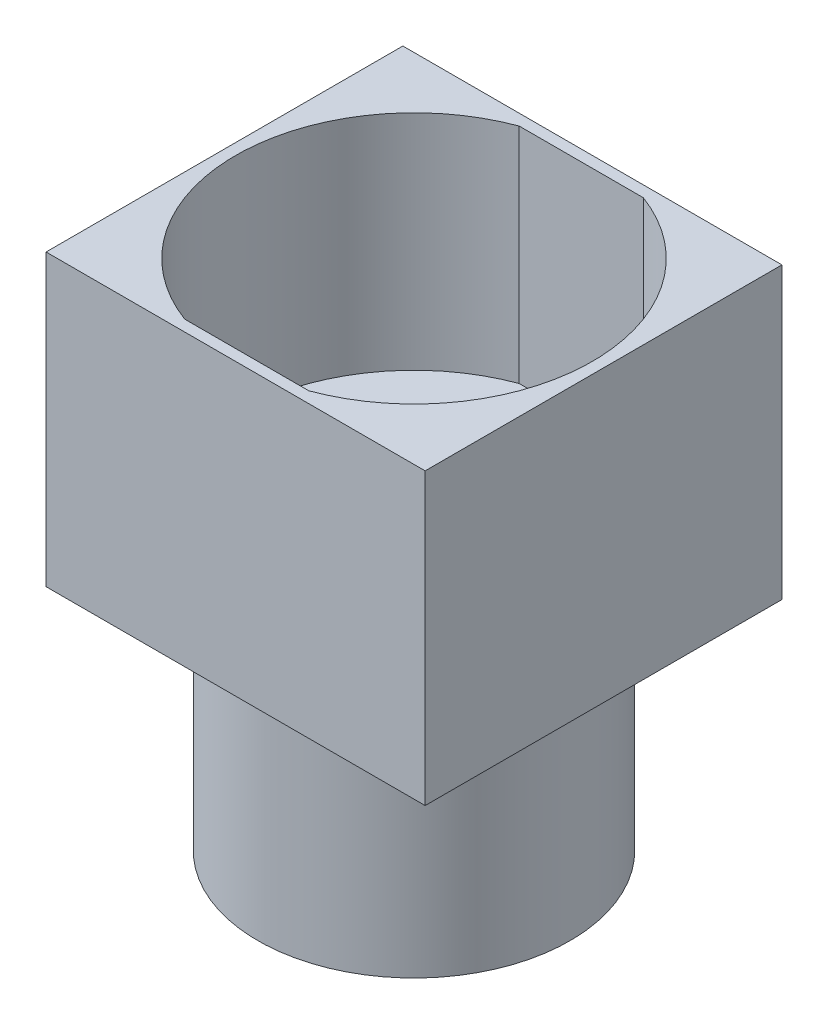
SolidWorks part; units mm, degrees
ref_plane "Front Plane" through (0, 0, 0) normal (0, 0, 1) x (1, 0, 0)
ref_plane "Top Plane" through (0, 0, 0) normal (0, 1, 0) x (1, 0, 0)
ref_plane "Right Plane" through (0, 0, 0) normal (1, 0, 0) x (0, 0, -1)
sketch "Sketch1" plane through (0, 0, 0) normal (0, 1, 0) x (1, 0, 0)
  circle A0 centre (0, 0) radius 4
  circle A1 centre (0, 0) radius 7
  dimension "D1" = 8
  dimension "D2" = 14
extrude "Boss-Extrude1" add sketch "Sketch1" along normal blind 13
sketch "Sketch2" plane through (0, 13, 0) normal (0, 1, 0) x (1, 0, 0)
  line L0 (-8, 7.5) -> (-8, -7.5) construction
  line L1 (-8.5, 8) -> (8.5, 8)
  line L2 (-8.5, 8) -> (-8.5, -8)
  line L3 (-8.5, -8) -> (8.5, -8)
  line L4 (8.5, 8) -> (8.5, -8)
  line L5 (-8.5, 8) -> (8.5, -8) construction
  line L6 (-8.5, -8) -> (8.5, 8) construction
  line L7 (-8, -7.5) -> (8, -7.5) construction
  line L8 (8, 7.5) -> (8, -7.5) construction
  line L9 (-8, 7.5) -> (8, 7.5) construction
  circle A0 centre (0, 0) radius 3.5
  point P0 (0, 0)
  dimension "D1" = 16
  dimension "D2" = 17
  dimension "D3" = 0.5
ref_plane "Plane1" through (0, 10, 0) normal (0, 1, 0) x (1, 0, 0)
sketch "Sketch5" plane through (0, 10, 0) normal (0, 1, 0) x (1, 0, 0)
  line L1 (-8.5, 8) -> (8.5, 8)
  line L2 (-8.5, 8) -> (-8.5, -8)
  line L3 (-8.5, -8) -> (8.5, -8)
  line L4 (8.5, 8) -> (8.5, -8)
extrude "Boss-Extrude3" add sketch "Sketch5" along normal blind 3
sketch "Sketch6" plane through (0, 13, 0) normal (0, 1, 0) x (1, 0, 0)
  line L1 (-8.5, 8) -> (8.5, 8)
  line L2 (-8.5, 8) -> (-8.5, -8)
  line L3 (-8.5, -8) -> (8.5, -8)
  line L5 (-2.7839, 7.5) -> (2.7839, 7.5)
  line L7 (-2.7839, -7.5) -> (2.7839, -7.5)
  arc A1 (-2.7839, 7.5) -> (-2.7839, -7.5) centre (0, 0) ccw
  arc A2 (2.7839, -7.5) -> (2.7839, 7.5) centre (0, 0) ccw
  line M9 (-8.5, 8) -> (-8.5, -8)
  line M10 (-8.5, -8) -> (8.5, -8)
  line M11 (8.5, -8) -> (8.5, 8)
  line M12 (8.5, 8) -> (-8.5, 8)
sketch "Sketch7" plane through (0, 13, 0) normal (0, 1, 0) x (1, 0, 0)
  circle A0 centre (0, 0) radius 4
extrude "Cut-Extrude2" cut sketch "Sketch7" against normal blind 14
extrude "Boss-Extrude5" add sketch "Sketch6" along normal blind 10 contours A2 L7 A1 L5 M12 M9 M10 M11
